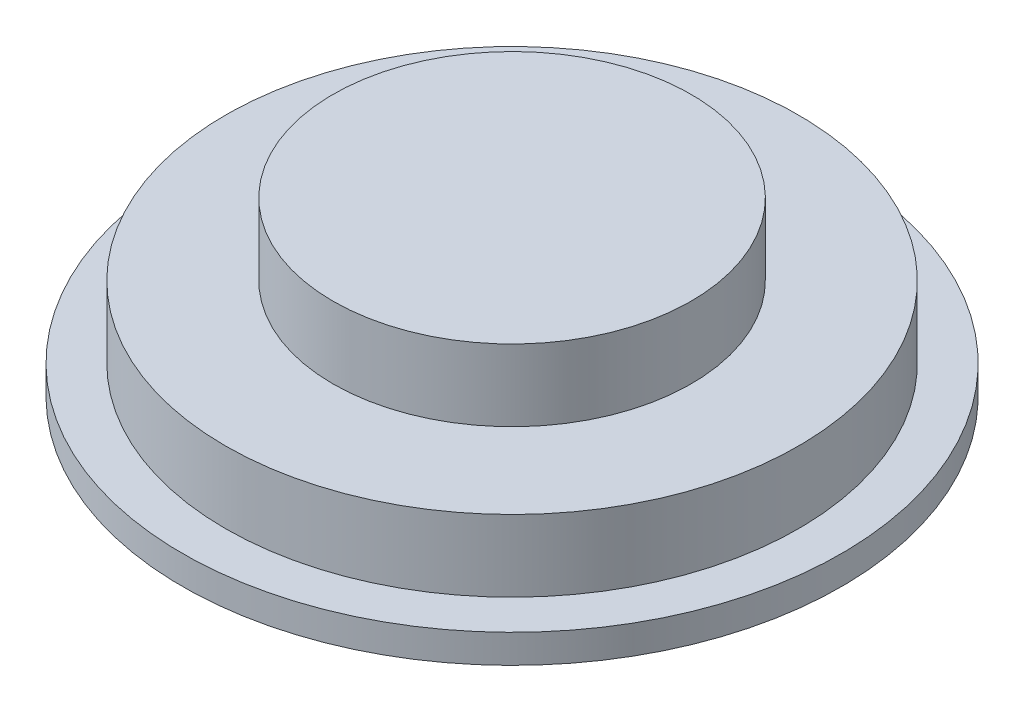
SolidWorks part; units mm, degrees
ref_plane "前视基准面" through (0, 0, 0) normal (0, 0, 1) x (1, 0, 0)
ref_plane "上视基准面" through (0, 0, 0) normal (0, 1, 0) x (1, 0, 0)
ref_plane "右视基准面" through (0, 0, 0) normal (1, 0, 0) x (0, 0, -1)
sketch "草图1" plane through (0, 0, 0) normal (0, 1, 0) x (1, 0, 0)
  circle A0 centre (0, 0) radius 20
  dimension "D1" = 40
extrude "凸台-拉伸1" add sketch "草图1" along normal blind 5
sketch "草图3" plane through (0, 0, 0) normal (0, -1, 0) x (1, 0, 0)
  circle A0 centre (0, 0) radius 17.5 construction
  circle A1 centre (0, 0) radius 23
  dimension "D1" = 35
  dimension "D2" = 46
extrude "凸台-拉伸3" add sketch "草图3" along normal blind 2
sketch "草图4" plane through (0, 5, 0) normal (0, 1, 0) x (1, 0, 0)
  circle A0 centre (0, 0) radius 12.5
  dimension "D1" = 25
extrude "凸台-拉伸4" add sketch "草图4" along normal blind 5
